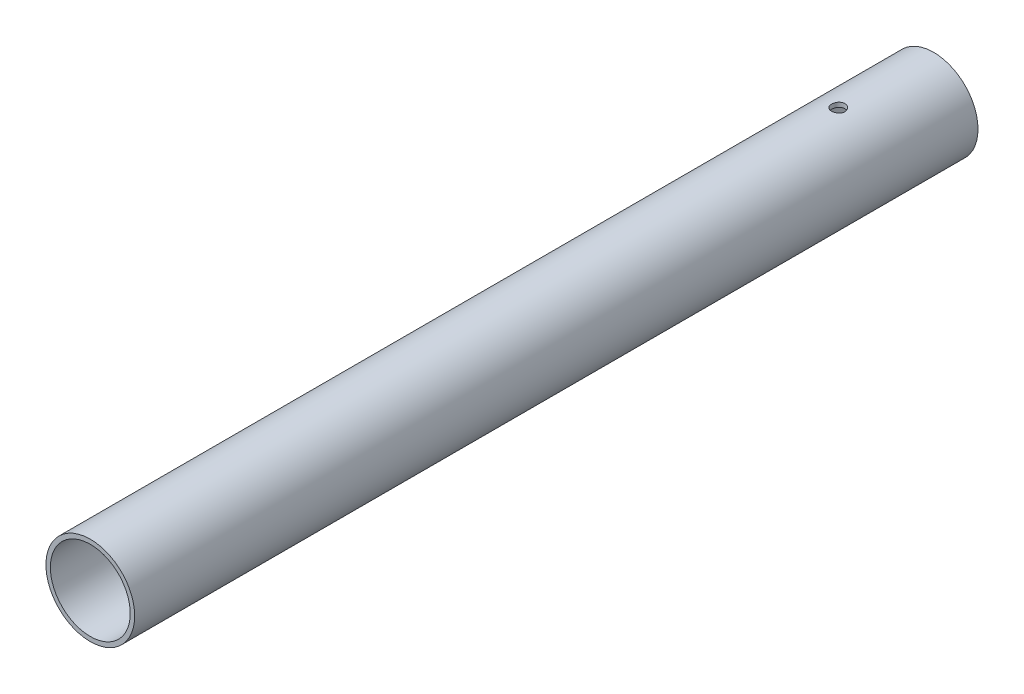
SolidWorks part; units mm, degrees
material "Thornel VCB-20 Carbon Cloth"
ref_plane "Front Plane" through (0, 0, 0) normal (0, 0, 1) x (1, 0, 0)
ref_plane "Top Plane" through (0, 0, 0) normal (0, 1, 0) x (1, 0, 0)
ref_plane "Right Plane" through (0, 0, 0) normal (1, 0, 0) x (0, 0, -1)
sketch "Sketch2" plane through (0, 0, 0) normal (0, 0, 1) x (1, 0, 0)
  circle A0 centre (0, 0) radius 10
  circle A1 centre (0, 0) radius 9
  dimension "D1" = 20
  dimension "D2" = 18
extrude "Boss-Extrude1" add sketch "Sketch2" along normal blind 190
sketch "Sketch3" plane through (0, 0, 0) normal (0, 1, 0) x (1, 0, 0)
  line L0 (10, 0) -> (-10, 0) construction
  circle A0 centre (0, -21.5) radius 1.5
  dimension "D2" = 3
  dimension "D1" = 21.5
extrude "Cut-Extrude1" cut sketch "Sketch3" against normal through all both and the other way through all
